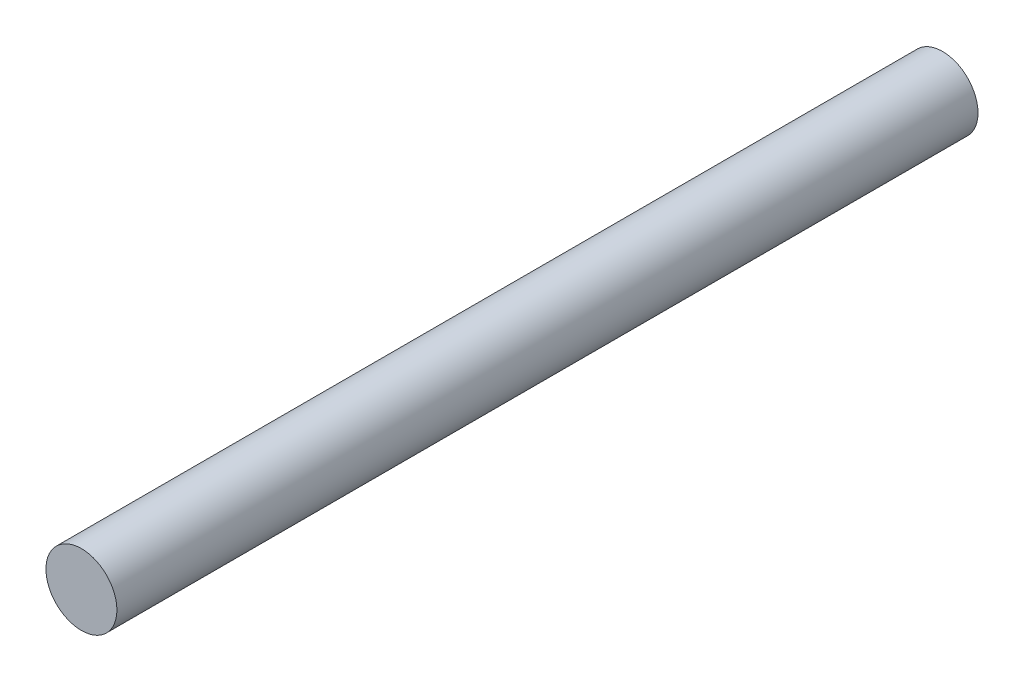
SolidWorks part; units mm, degrees
ref_plane "前视基准面" through (0, 0, 0) normal (0, 0, 1) x (1, 0, 0)
ref_plane "上视基准面" through (0, 0, 0) normal (0, 1, 0) x (1, 0, 0)
ref_plane "右视基准面" through (0, 0, 0) normal (1, 0, 0) x (0, 0, -1)
other "Configuration Table"
sketch "草图2" plane through (0, 0, 0) normal (0, 0, 1) x (1, 0, 0)
  circle A0 centre (0, 0) radius 0.75
extrude "凸台-拉伸1" add sketch "草图2" along normal blind 18.2
